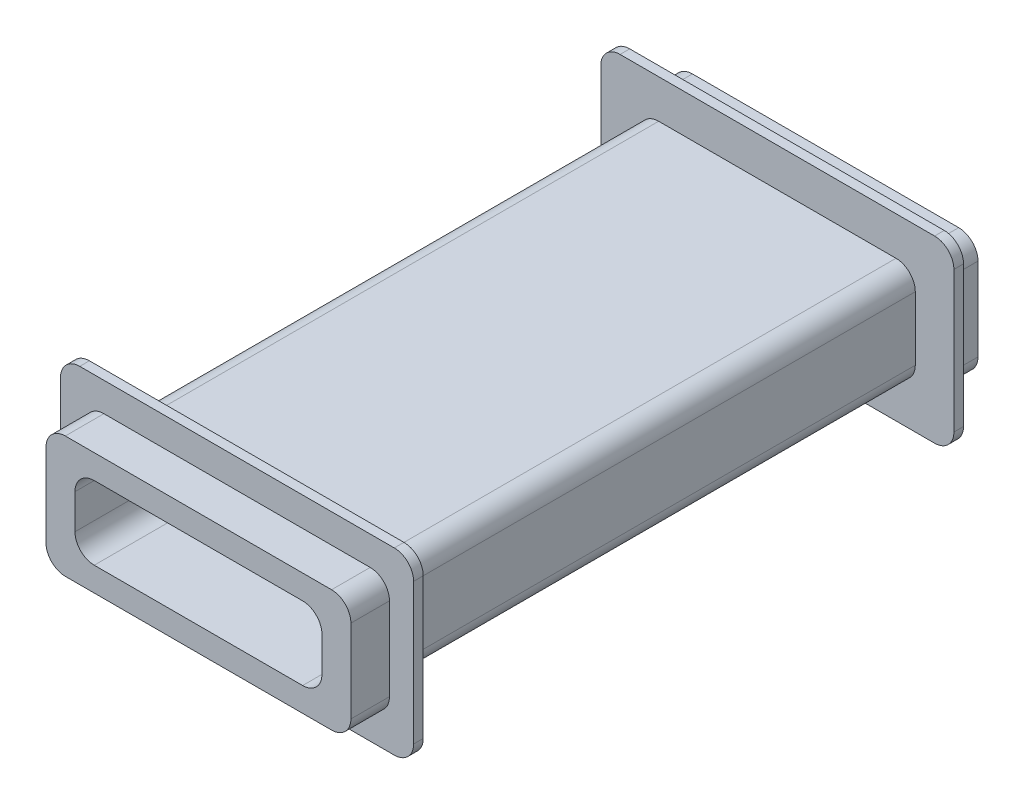
SolidWorks part; units mm, degrees
material "7079 Alloy"
ref_plane "Front Plane" through (0, 0, 0) normal (0, 0, 1) x (1, 0, 0)
ref_plane "Top Plane" through (0, 0, 0) normal (0, 1, 0) x (1, 0, 0)
ref_plane "Right Plane" through (0, 0, 0) normal (1, 0, 0) x (0, 0, -1)
sketch "Sketch1" plane through (0, 0, 0) normal (0, 0, 1) x (1, 0, 0)
  line L1 (-12.8, -3.8) -> (12.8, -3.8)
  line L2 (-12.8, -3.8) -> (-12.8, 3.8)
  line L3 (-12.8, 3.8) -> (12.8, 3.8)
  line L4 (12.8, -3.8) -> (12.8, 3.8)
  line L5 (-12.8, -3.8) -> (12.8, 3.8) construction
  line L6 (-12.8, 3.8) -> (12.8, -3.8) construction
  line L7 (-14.3, -5.3) -> (14.3, -5.3)
  line L8 (-14.3, -5.3) -> (-14.3, 5.3)
  line L9 (-14.3, 5.3) -> (14.3, 5.3)
  line L10 (14.3, -5.3) -> (14.3, 5.3)
  line L11 (-14.3, -5.3) -> (14.3, 5.3) construction
  line L12 (-14.3, 5.3) -> (14.3, -5.3) construction
  point P0 (0, 0)
  point P6 (0, 0)
  dimension "D1" = 1.5
  dimension "D2" = 1.5
  dimension "D3" = 10.6
  dimension "D4" = 25.6
extrude "Boss-Extrude1" add sketch "Sketch1" along normal blind 55
sketch "Sketch2" plane through (0, 0, 55) normal (0, 0, 1) x (1, 0, 0)
  line L0 (14.3, 5.3) -> (-14.3, 5.3) construction
  line L1 (-18.3, -9.3) -> (18.3, -9.3)
  line L2 (-18.3, -9.3) -> (-18.3, 9.3)
  line L3 (-18.3, 9.3) -> (18.3, 9.3)
  line L4 (18.3, -9.3) -> (18.3, 9.3)
  line L5 (-18.3, -9.3) -> (18.3, 9.3) construction
  line L6 (-18.3, 9.3) -> (18.3, -9.3) construction
  line L7 (-14.3, 5.3) -> (-14.3, -5.3) construction
  line L9 (-12.8, -3.8) -> (12.8, -3.8)
  line L10 (-12.8, -3.8) -> (-12.8, 3.8)
  line L11 (-12.8, 3.8) -> (12.8, 3.8)
  line L12 (12.8, -3.8) -> (12.8, 3.8)
  line L13 (-12.8, -3.8) -> (12.8, 3.8) construction
  line L14 (-12.8, 3.8) -> (12.8, -3.8) construction
  point P0 (0, 0)
  point P10 (0, 0)
  dimension "D1" = 4
  dimension "D2" = 4
extrude "Boss-Extrude3" add sketch "Sketch2" along normal blind 1
sketch "Sketch3" plane through (0, 0, 56) normal (0, 0, 1) x (1, 0, 0)
  line L0 (-12.8, 3.8) -> (-12.8, -3.8) construction
  line L1 (-15.8, -6.3) -> (15.8, -6.3)
  line L2 (-15.8, -6.3) -> (-15.8, 6.3)
  line L3 (-15.8, 6.3) -> (15.8, 6.3)
  line L4 (15.8, -6.3) -> (15.8, 6.3)
  line L5 (-15.8, -6.3) -> (15.8, 6.3) construction
  line L6 (-15.8, 6.3) -> (15.8, -6.3) construction
  line L7 (-12.8, -3.8) -> (12.8, -3.8) construction
  line L8 (12.8, -3.8) -> (12.8, 3.8) construction
  line L9 (12.8, 3.8) -> (-12.8, 3.8) construction
  line L10 (-12.8, 3.8) -> (-12.8, -3.8)
  line L11 (-12.8, -3.8) -> (12.8, -3.8)
  line L12 (12.8, -3.8) -> (12.8, 3.8)
  line L13 (12.8, 3.8) -> (-12.8, 3.8)
  point P0 (0, 0)
  dimension "D1" = 2.5
  dimension "D2" = 3
extrude "Boss-Extrude4" add sketch "Sketch3" along normal blind 4
ref_plane "Plane1" through (0, 0, 27.5) normal (0, 0, -1) x (-1, 0, 0)
mirror "Mirror1" about plane through (0, 0, 27.5) normal (0, 0, -1) of "Boss-Extrude4", "Boss-Extrude3"
fillet "Fillet1" radius 2 16 edges at (-15.8, -6.3, -3) (15.8, -6.3, -3) (-15.8, 6.3, -3) (15.8, 6.3, -3) (12.8, -3.8, 27.5) (-12.8, -3.8, 27.5) (12.8, 3.8, 27.5) (-12.8, 3.8, 27.5) (-14.3, -5.3, 27.5) (-14.3, 5.3, 27.5) (14.3, -5.3, 27.5) (14.3, 5.3, 27.5) (15.8, -6.3, 58) (15.8, 6.3, 58) (-15.8, -6.3, 58) (-15.8, 6.3, 58)
fillet "Fillet2" radius 2 8 edges at (-18.3, 9.3, 55.5) (18.3, 9.3, 55.5) (18.3, -9.3, 55.5) (-18.3, -9.3, 55.5) (-18.3, -9.3, -0.5) (-18.3, 9.3, -0.5) (18.3, -9.3, -0.5) (18.3, 9.3, -0.5)
